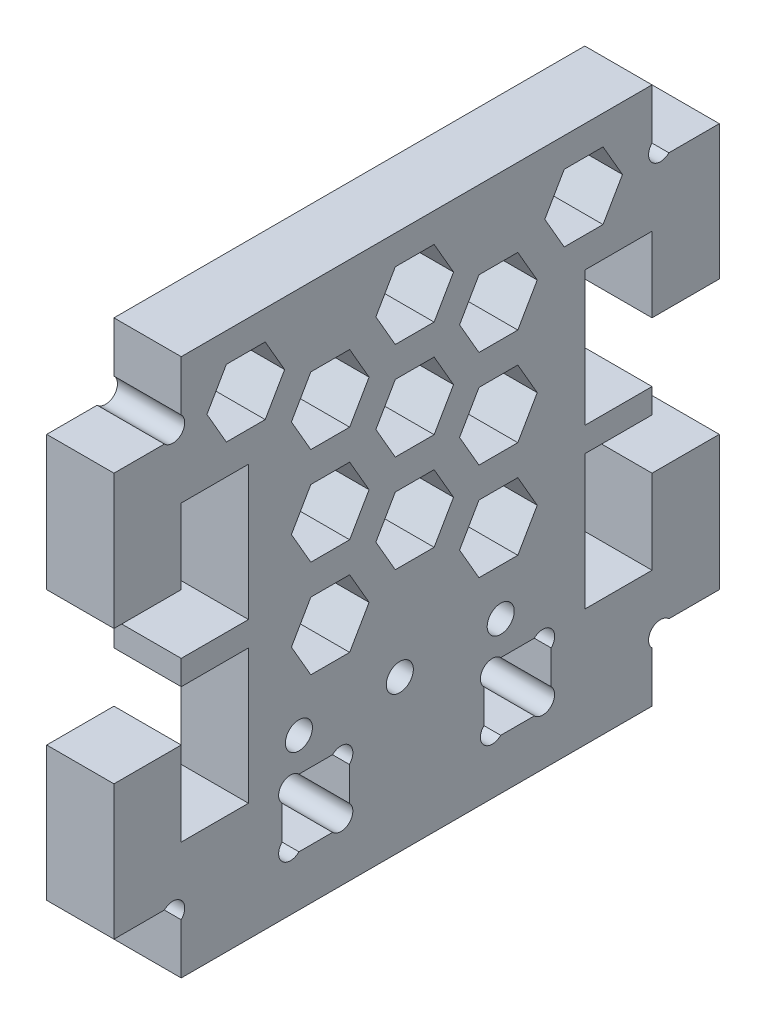
SolidWorks part; units mm, degrees
material "6061 Alloy"
ref_plane "Front" through (0, 0, 0) normal (0, 0, 1) x (1, 0, 0)
ref_plane "Top" through (0, 0, 0) normal (0, 1, 0) x (1, 0, 0)
ref_plane "Right" through (0, 0, 0) normal (1, 0, 0) x (0, 0, -1)
sketch "Sketch3" plane through (0, 0, 0) normal (1, 0, 0) x (0, 0, -1)
  line L1 (-44.45, -50.8) -> (44.45, -50.8)
  line L2 (-44.45, -50.8) -> (-44.45, 50.8)
  line L3 (-44.45, 50.8) -> (44.45, 50.8)
  line L4 (44.45, -50.8) -> (44.45, 50.8)
  line L5 (-44.45, -50.8) -> (44.45, 50.8) construction
  line L6 (-44.45, 50.8) -> (44.45, -50.8) construction
  point P0 (0, 0)
  dimension "D1" = 88.9
  dimension "D2" = 101.6
extrude "Square Extrusion" add sketch "Sketch3" along normal blind 12.7
sketch "Sketch4" plane through (12.7, 0, 0) normal (1, 0, 0) x (0, 0, -1)
  line L0 (-44.45, -50.8) -> (-19.05, -50.8) construction
  line L1 (-44.45, -50.8) -> (44.45, -50.8) construction
  line L2 (-19.05, -50.8) -> (-19.05, -34.925) construction
  line L3 (0, -50.8) -> (0, 50.8) construction
  line L4 (-25.4, -41.275) -> (-12.7, -41.275)
  line L5 (-25.4, -41.275) -> (-25.4, -28.575)
  line L6 (-25.4, -28.575) -> (-12.7, -28.575)
  line L7 (-12.7, -41.275) -> (-12.7, -28.575)
  line L8 (-25.4, -41.275) -> (-12.7, -28.575) construction
  line L9 (-25.4, -28.575) -> (-12.7, -41.275) construction
  line L10 (44.45, 50.8) -> (-44.45, 50.8) construction
  line L11 (25.4, -28.575) -> (12.7, -28.575)
  line L12 (12.7, -41.275) -> (12.7, -28.575)
  line L13 (25.4, -41.275) -> (12.7, -41.275)
  line L14 (25.4, -41.275) -> (25.4, -28.575)
  line L15 (-25.4, -34.925) -> (-12.7, -34.925) construction
  circle A0 centre (-14.2875, -30.1625) radius 2.2454
  circle A1 centre (-23.8125, -30.1625) radius 2.2454
  circle A2 centre (-14.2875, -39.6875) radius 2.2454
  circle A3 centre (-23.8125, -39.6875) radius 2.2454
  circle A4 centre (23.8125, -39.6875) radius 2.2454
  circle A5 centre (14.2875, -39.6875) radius 2.2454
  circle A6 centre (14.2875, -30.1625) radius 2.2454
  circle A7 centre (23.8125, -30.1625) radius 2.2454
  dimension "D7" = 4.4907
  dimension "D1" = 25.4
  dimension "D2" = 9.525
  dimension "D3" = 12.7
  dimension "D4" = 12.7
  dimension "D5" = 1.5875
extrude "Slotting Holes" cut sketch "Sketch4" against normal up to surface (12.7 mm away) contours A1 L5 L6 | A1 L6 L5 | A3 L4 A2 L7 A0 L6 A1 L5 | L6 A0 L7 | L7 A0 L6 | L4 A3 L5 | L5 A3 L4 | A2 L4 L7 | A2 L7 L4 | A6 L12 L11 | A6 L11 L12 | A7 L11 A6 L12 A5 L13 A4 L14 | L11 A7 L14 | L14 A7 L11 | A4 L13 L14 | A4 L14 L13 | L13 A5 L12 | L12 A5 L13 up to face at (0, 0, 0)
sketch "Sketch9" plane through (12.7, 0, 0) normal (1, 0, 0) x (0, 0, -1)
  line L96 (0, 0) -> (0, 11.43) construction
  line L97 (0, 6.985) -> (0, -6.985) construction
  line L111 (6.9677, 38.9312) -> (3.3015, 45.2812)
  line L112 (-24.9281, 38.9312) -> (-28.5942, 45.2812)
  line L113 (-28.5942, 45.2812) -> (-35.9266, 45.2812)
  line L114 (-35.9266, 45.2812) -> (-39.5928, 38.9312)
  line L115 (-39.5928, 38.9312) -> (-35.9266, 32.5812)
  line L116 (-35.9266, 32.5812) -> (-28.5942, 32.5812)
  line L117 (-28.5942, 32.5812) -> (-24.9281, 38.9312)
  line L118 (3.3015, 45.2812) -> (-4.0309, 45.2812)
  line L119 (-4.0309, 45.2812) -> (-7.697, 38.9312)
  line L120 (-7.697, 38.9312) -> (-4.0309, 32.5812)
  line L121 (-4.0309, 32.5812) -> (3.3015, 32.5812)
  line L122 (3.3015, 32.5812) -> (6.9677, 38.9312)
  line L123 (38.8634, 38.9312) -> (35.1972, 45.2812)
  line L124 (35.1972, 45.2812) -> (27.8648, 45.2812)
  line L125 (27.8648, 45.2812) -> (24.1987, 38.9312)
  line L126 (24.1987, 38.9312) -> (27.8648, 32.5812)
  line L127 (27.8648, 32.5812) -> (35.1972, 32.5812)
  line L128 (35.1972, 32.5812) -> (38.8634, 38.9312)
  line L129 (-8.9802, 29.7237) -> (-12.6464, 36.0737)
  line L130 (-12.6464, 36.0737) -> (-19.9787, 36.0737)
  line L131 (-19.9787, 36.0737) -> (-23.6449, 29.7237)
  line L132 (-23.6449, 29.7237) -> (-19.9787, 23.3737)
  line L133 (-19.9787, 23.3737) -> (-12.6464, 23.3737)
  line L134 (-12.6464, 23.3737) -> (-8.9802, 29.7237)
  line L135 (22.7698, 29.7237) -> (19.1036, 36.0737)
  line L136 (19.1036, 36.0737) -> (11.7713, 36.0737)
  line L137 (11.7713, 36.0737) -> (8.1051, 29.7237)
  line L138 (8.1051, 29.7237) -> (11.7713, 23.3737)
  line L139 (11.7713, 23.3737) -> (19.1036, 23.3737)
  line L140 (19.1036, 23.3737) -> (22.7698, 29.7237)
  line L141 (-24.9281, 20.5162) -> (-28.5942, 26.8662)
  line L142 (-28.5942, 26.8662) -> (-35.9266, 26.8662)
  line L143 (-35.9266, 26.8662) -> (-39.5928, 20.5162)
  line L144 (-39.5928, 20.5162) -> (-35.9266, 14.1662)
  line L145 (-35.9266, 14.1662) -> (-28.5942, 14.1662)
  line L146 (-28.5942, 14.1662) -> (-24.9281, 20.5162)
  line L147 (6.9677, 20.5162) -> (3.3015, 26.8662)
  line L148 (3.3015, 26.8662) -> (-4.0309, 26.8662)
  line L149 (-4.0309, 26.8662) -> (-7.697, 20.5162)
  line L150 (-7.697, 20.5162) -> (-4.0309, 14.1662)
  line L151 (-4.0309, 14.1662) -> (3.3015, 14.1662)
  line L152 (3.3015, 14.1662) -> (6.9677, 20.5162)
  line L153 (38.8634, 20.5162) -> (35.1972, 26.8662)
  line L154 (35.1972, 26.8662) -> (27.8648, 26.8662)
  line L155 (27.8648, 26.8662) -> (24.1987, 20.5162)
  line L156 (24.1987, 20.5162) -> (27.8648, 14.1662)
  line L157 (27.8648, 14.1662) -> (35.1972, 14.1662)
  line L158 (35.1972, 14.1662) -> (38.8634, 20.5162)
  line L159 (-24.9281, 2.1012) -> (-28.5942, 8.4512)
  line L160 (-28.5942, 8.4512) -> (-35.9266, 8.4512)
  line L161 (-35.9266, 8.4512) -> (-39.5928, 2.1012)
  line L162 (-39.5928, 2.1012) -> (-35.9266, -4.2488)
  line L163 (-35.9266, -4.2488) -> (-28.5942, -4.2488)
  line L164 (-28.5942, -4.2488) -> (-24.9281, 2.1012)
  line L165 (-8.9802, -7.1063) -> (-12.6464, -0.7563)
  line L166 (-12.6464, -0.7563) -> (-19.9787, -0.7563)
  line L167 (-19.9787, -0.7563) -> (-23.6449, -7.1063)
  line L168 (-23.6449, -7.1063) -> (-19.9787, -13.4563)
  line L169 (-19.9787, -13.4563) -> (-12.6464, -13.4563)
  line L170 (-12.6464, -13.4563) -> (-8.9802, -7.1063)
  line L171 (6.9677, 2.1012) -> (3.3015, 8.4512)
  line L172 (3.3015, 8.4512) -> (-4.0309, 8.4512)
  line L173 (-4.0309, 8.4512) -> (-7.697, 2.1012)
  line L174 (-7.697, 2.1012) -> (-4.0309, -4.2488)
  line L175 (-4.0309, -4.2488) -> (3.3015, -4.2488)
  line L176 (3.3015, -4.2488) -> (6.9677, 2.1012)
  line L177 (22.7698, -7.1063) -> (19.1036, -0.7563)
  line L178 (19.1036, -0.7563) -> (11.7713, -0.7563)
  line L179 (11.7713, -0.7563) -> (8.1051, -7.1063)
  line L180 (8.1051, -7.1063) -> (11.7713, -13.4563)
  line L181 (11.7713, -13.4563) -> (19.1036, -13.4563)
  line L182 (19.1036, -13.4563) -> (22.7698, -7.1063)
  line L183 (38.8634, 2.1012) -> (35.1972, 8.4512)
  line L184 (35.1972, 8.4512) -> (27.8648, 8.4512)
  line L185 (27.8648, 8.4512) -> (24.1987, 2.1012)
  line L186 (24.1987, 2.1012) -> (27.8648, -4.2488)
  line L187 (27.8648, -4.2488) -> (35.1972, -4.2488)
  line L188 (35.1972, -4.2488) -> (38.8634, 2.1012)
  line L189 (38.8634, -16.3138) -> (35.1972, -9.9638)
  line L190 (35.1972, -9.9638) -> (27.8648, -9.9638)
  line L191 (27.8648, -9.9638) -> (24.1987, -16.3138)
  line L192 (24.1987, -16.3138) -> (27.8648, -22.6638)
  line L193 (27.8648, -22.6638) -> (35.1972, -22.6638)
  line L194 (35.1972, -22.6638) -> (38.8634, -16.3138)
  line L195 (6.9677, -16.3138) -> (3.3015, -9.9638)
  line L196 (-4.0309, -9.9638) -> (-7.697, -16.3138)
  line L197 (-7.697, -16.3138) -> (-4.0309, -22.6638)
  line L198 (-4.0309, -22.6638) -> (3.3015, -22.6638)
  line L199 (3.3015, -22.6638) -> (6.9677, -16.3138)
  line L200 (3.3015, -9.9638) -> (-4.0309, -9.9638)
  line L201 (-24.9281, -16.3138) -> (-28.5942, -9.9638)
  line L202 (-28.5942, -9.9638) -> (-35.9266, -9.9638)
  line L203 (-35.9266, -9.9638) -> (-39.5928, -16.3138)
  line L204 (-39.5928, -16.3138) -> (-35.9266, -22.6638)
  line L205 (-35.9266, -22.6638) -> (-28.5942, -22.6638)
  line L206 (-28.5942, -22.6638) -> (-24.9281, -16.3138)
  line L207 (22.7698, 11.3087) -> (19.1036, 17.6587)
  line L208 (19.1036, 17.6587) -> (11.7713, 17.6587)
  line L209 (11.7713, 17.6587) -> (8.1051, 11.3087)
  line L210 (8.1051, 11.3087) -> (11.7713, 4.9587)
  line L211 (11.7713, 4.9587) -> (19.1036, 4.9587)
  line L212 (19.1036, 4.9587) -> (22.7698, 11.3087)
  line L213 (-8.9802, 11.3087) -> (-12.6464, 17.6587)
  line L214 (-12.6464, 17.6587) -> (-19.9787, 17.6587)
  line L215 (-19.9787, 17.6587) -> (-23.6449, 11.3087)
  line L216 (-23.6449, 11.3087) -> (-19.9787, 4.9587)
  line L217 (-19.9787, 4.9587) -> (-12.6464, 4.9587)
  line L218 (-12.6464, 4.9587) -> (-8.9802, 11.3087)
  circle A0 centre (-32.2604, 38.9312) radius 6.35 construction
  circle A1 centre (-0.3647, 38.9312) radius 6.35 construction
  circle A2 centre (31.531, 38.9312) radius 6.35 construction
  circle A3 centre (-16.3126, 29.7237) radius 6.35 construction
  circle A4 centre (15.4374, 29.7237) radius 6.35 construction
  circle A5 centre (-32.2604, 20.5162) radius 6.35 construction
  circle A6 centre (-0.3647, 20.5162) radius 6.35 construction
  circle A7 centre (31.531, 20.5162) radius 6.35 construction
  circle A8 centre (-32.2604, 2.1012) radius 6.35 construction
  circle A9 centre (-16.3126, -7.1063) radius 6.35 construction
  circle A10 centre (-0.3647, 2.1012) radius 6.35 construction
  circle A11 centre (15.4374, -7.1063) radius 6.35 construction
  circle A12 centre (31.531, 2.1012) radius 6.35 construction
  circle A13 centre (31.531, -16.3138) radius 6.35 construction
  circle A14 centre (-0.3647, -16.3138) radius 6.35 construction
  circle A15 centre (-32.2604, -16.3138) radius 6.35 construction
  circle A16 centre (-16.3126, 11.3087) radius 6.35 construction
  circle A17 centre (15.4374, 11.3087) radius 6.35 construction
  dimension "D1" = 11.43
extrude "Honeycomb Pocketing" cut sketch "Sketch9" against normal up to surface (12.7 mm away) contours L116 L117 L112 L113 L114 L115 | L121 L122 L111 L118 L119 L120 | L127 L128 L123 L124 L125 L126 | L133 L134 L129 L130 L131 L132 | L139 L140 L135 L136 L137 L138 | L151 L152 L147 L148 L149 L150 | L217 L218 L213 L214 L215 L216 | L211 L212 L207 L208 L209 L210 | L175 L176 L171 L172 L173 L174 | L169 L170 L165 L166 L167 L168 | L181 L182 L177 L178 L179 L180 up to face at (0, -34.925, 19.05)
sketch "Sketch10" plane through (12.7, 0, 0) normal (1, 0, 0) x (0, 0, -1)
  line L0 (-44.45, 0) -> (44.45, 0) construction
  line L1 (-44.45, 0) -> (-44.45, 50.8) construction
  line L2 (-44.45, 25.4) -> (-57.15, 25.4)
  line L3 (-44.45, 25.4) -> (-44.45, 38.1)
  line L4 (-44.45, 38.1) -> (-57.15, 38.1)
  line L5 (-57.15, 25.4) -> (-57.15, 38.1)
  line L6 (-57.15, 25.4) -> (-44.45, 25.4)
  line L7 (-57.15, 25.4) -> (-57.15, 12.7)
  line L8 (-57.15, 12.7) -> (-44.45, 12.7)
  line L9 (-44.45, 25.4) -> (-44.45, 12.7)
  line L10 (44.45, -50.8) -> (44.45, 50.8) construction
  line L11 (-57.15, -12.7) -> (-44.45, -12.7)
  line L12 (-44.45, -25.4) -> (-44.45, -12.7)
  line L13 (-57.15, -25.4) -> (-44.45, -25.4)
  line L14 (-57.15, -25.4) -> (-57.15, -12.7)
  line L15 (-44.45, -38.1) -> (-57.15, -38.1)
  line L16 (-57.15, -25.4) -> (-57.15, -38.1)
  line L17 (-44.45, -25.4) -> (-57.15, -25.4)
  line L18 (-44.45, -25.4) -> (-44.45, -38.1)
  line L19 (0, 50.8) -> (0, -50.8) construction
  line L20 (44.45, 50.8) -> (-44.45, 50.8) construction
  line L21 (-44.45, -50.8) -> (44.45, -50.8) construction
  line L22 (44.45, -38.1) -> (57.15, -38.1)
  line L23 (57.15, -25.4) -> (57.15, -38.1)
  line L24 (57.15, -25.4) -> (44.45, -25.4)
  line L25 (57.15, -25.4) -> (57.15, -12.7)
  line L26 (57.15, -12.7) -> (44.45, -12.7)
  line L27 (44.45, -25.4) -> (44.45, -12.7)
  line L28 (44.45, -25.4) -> (44.45, -38.1)
  line L29 (57.15, 12.7) -> (44.45, 12.7)
  line L30 (44.45, 25.4) -> (44.45, 12.7)
  line L31 (57.15, 25.4) -> (44.45, 25.4)
  line L32 (57.15, 25.4) -> (57.15, 12.7)
  line L33 (44.45, 38.1) -> (57.15, 38.1)
  line L34 (57.15, 25.4) -> (57.15, 38.1)
  line L35 (44.45, 25.4) -> (57.15, 25.4)
  line L36 (44.45, 25.4) -> (44.45, 38.1)
  line L37 (-63.5, 38.1) -> (-50.8, 38.1)
  line L43 (-63.5, 12.7) -> (-50.8, 12.7)
  line L46 (-44.45, 40.4795) -> (-44.45, 38.1)
  line L47 (-44.45, 12.7) -> (-44.45, 10.7537)
  line L48 (-44.45, -10.7537) -> (-44.45, -12.7)
  line L49 (-44.45, 50.8) -> (-44.45, -50.8) construction
  line L50 (-44.45, -40.4795) -> (-44.45, -38.1)
  line L51 (44.45, -40.4795) -> (44.45, -38.1)
  line L52 (44.45, -10.7537) -> (44.45, -12.7)
  line L53 (44.45, 12.7) -> (44.45, 10.7537)
  line L54 (44.45, 40.4795) -> (44.45, 38.1)
  point P43 (44.45, 50.8)
  dimension "D4" = 12.7
  dimension "D1" = 12.7
  dimension "D2" = 12.7
  dimension "D3" = 12.7
extrude "Side Slots" add sketch "Sketch10" against normal blind 12.7 contours L5 L2 L3 L4 | L9 L2 L7 L8 | L14 L13 L12 L11 | L18 L13 L16 L15 | L27 L24 L25 L26 | L24 L28 L22 L23 | L32 L31 L30 L29 | L36 L31 L34 L33
sketch "Sketch12" plane through (12.7, 0, 0) normal (1, 0, 0) x (0, 0, -1)
  line L0 (-44.45, 50.8) -> (-44.45, 38.1) construction
  line L1 (-44.45, 38.1) -> (-57.15, 38.1) construction
  line L2 (-57.15, 25.4) -> (57.15, 25.4) construction
  line L3 (-57.15, 12.7) -> (-57.15, 38.1) construction
  line L4 (57.15, 38.1) -> (57.15, 12.7) construction
  line L5 (0, 50.8) -> (0, -50.8) construction
  line L6 (44.45, 50.8) -> (-44.45, 50.8) construction
  line L7 (-44.45, -50.8) -> (44.45, -50.8) construction
  line L8 (-44.45, 0) -> (44.45, 0) construction
  line L9 (-44.45, 12.7) -> (-44.45, -12.7) construction
  line L10 (44.45, -12.7) -> (44.45, 12.7) construction
  circle A0 centre (-22.225, -22.225) radius 2.5527
  circle A1 centre (-3.175, -22.225) radius 2.5527
  circle A2 centre (15.875, -22.225) radius 2.5527
  circle A4 centre (-46.0375, 39.6875) radius 2.2454
  circle A5 centre (-46.0375, 11.1125) radius 2.2454
  circle A6 centre (46.0375, 11.1125) radius 2.2454
  circle A7 centre (46.0375, 39.6875) radius 2.2454
  circle A8 centre (46.0375, -11.1125) radius 2.2454
  circle A9 centre (46.0375, -39.6875) radius 2.2454
  circle A10 centre (-46.0375, -39.6875) radius 2.2454
  circle A11 centre (-46.0375, -11.1125) radius 2.2454
  dimension "D3" = 4.4907
  dimension "D1" = 1.5875
  dimension "D2" = 1.5875
extrude "Cut-Extrude1" cut sketch "Sketch12" against normal through all contours A4 | A10 | A0 | A1 | A2 | A9 | A7
sketch "Sketch14" plane through (12.7, 0, 0) normal (1, 0, 0) x (0, 0, -1)
  line L0 (-44.45, 0) -> (-44.45, -28.575) construction
  line L2 (-19.05, -28.575) -> (-44.45, -28.575) construction
  line L3 (-22.2246, -28.575) -> (-15.8754, -28.575) construction
  line L4 (-38.1, -3.175) -> (-38.1, 1.4662) construction
  line L5 (-44.45, -28.575) -> (-31.75, -28.575)
  line L6 (-44.45, -28.575) -> (-44.45, -3.175)
  line L7 (-44.45, -3.175) -> (-31.75, -3.175)
  line L8 (-31.75, -28.575) -> (-31.75, -3.175)
  line L9 (0, 19.6273) -> (0, 2.3112) construction
  line L10 (-31.75, 1.4662) -> (-44.45, 1.4662)
  line L11 (-31.75, 1.4662) -> (-31.75, 26.8662)
  line L12 (-31.75, 26.8662) -> (-44.45, 26.8662)
  line L13 (-44.45, 1.4662) -> (-44.45, 26.8662)
  line L14 (44.45, -3.175) -> (31.75, -3.175)
  line L15 (31.75, -28.575) -> (31.75, -3.175)
  line L16 (44.45, -28.575) -> (31.75, -28.575)
  line L17 (44.45, -28.575) -> (44.45, -3.175)
  line L18 (31.75, 26.8662) -> (44.45, 26.8662)
  line L19 (44.45, 1.4662) -> (44.45, 26.8662)
  line L20 (31.75, 1.4662) -> (44.45, 1.4662)
  line L21 (31.75, 1.4662) -> (31.75, 26.8662)
  dimension "D1" = 25.4
  dimension "D2" = 4.6412
  dimension "D3" = 25.4
extrude "Cut-Extrude4" cut sketch "Sketch14" against normal through all
